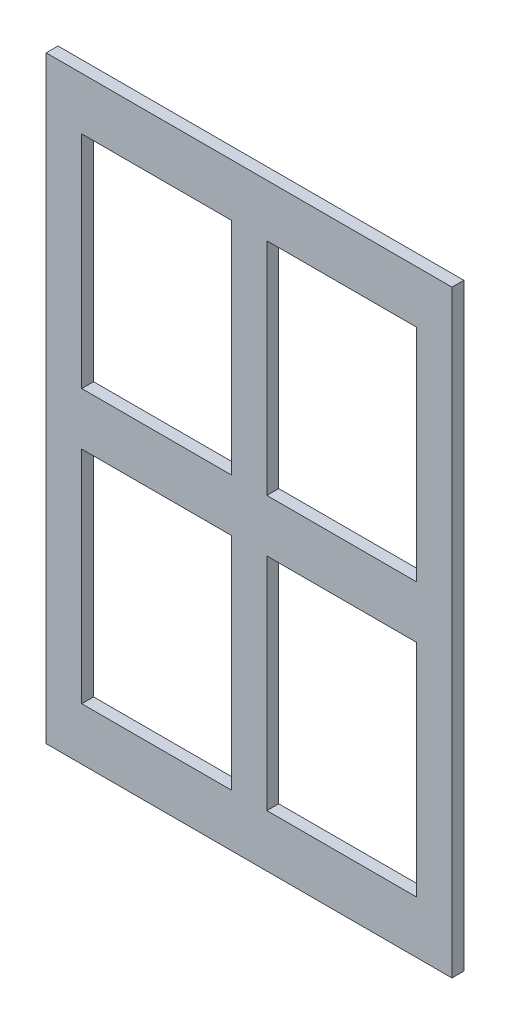
SolidWorks part; units mm, degrees
ref_plane "Front Plane" through (0, 0, 0) normal (0, 0, 1) x (1, 0, 0)
ref_plane "Top Plane" through (0, 0, 0) normal (0, 1, 0) x (1, 0, 0)
ref_plane "Right Plane" through (0, 0, 0) normal (1, 0, 0) x (0, 0, -1)
sketch "Sketch1" plane through (0, 0, 0) normal (0, 0, 1) x (1, 0, 0)
  line L1 (-68.5, -101) -> (68.5, -101)
  line L2 (-68.5, -101) -> (-68.5, 101)
  line L3 (-68.5, 101) -> (68.5, 101)
  line L4 (68.5, -101) -> (68.5, 101)
  line L5 (-68.5, -101) -> (68.5, 101) construction
  line L6 (-68.5, 101) -> (68.5, -101) construction
  line L7 (-56.5, 83.3066) -> (-6, 83.3066)
  line L8 (-56.5, 83.3066) -> (-56.5, 8.8467)
  line L9 (-56.5, 8.8467) -> (-6, 8.8467)
  line L10 (-6, 83.3066) -> (-6, 8.8467)
  line L11 (-56.5, 83.3066) -> (-6, 8.8467) construction
  line L12 (-56.5, 8.8467) -> (-6, 83.3066) construction
  line L13 (56.5, 83.3066) -> (6, 83.3066)
  line L14 (56.5, 83.3066) -> (56.5, 8.8467)
  line L15 (56.5, 8.8467) -> (6, 8.8467)
  line L16 (6, 83.3066) -> (6, 8.8467)
  line L17 (56.5, 83.3066) -> (6, 8.8467) construction
  line L18 (56.5, 8.8467) -> (6, 83.3066) construction
  line L19 (-56.5, -83.3066) -> (-6, -83.3066)
  line L20 (-56.5, -83.3066) -> (-56.5, -8.8467)
  line L21 (-56.5, -8.8467) -> (-6, -8.8467)
  line L22 (-6, -83.3066) -> (-6, -8.8467)
  line L23 (-56.5, -83.3066) -> (-6, -8.8467) construction
  line L24 (-56.5, -8.8467) -> (-6, -83.3066) construction
  line L25 (56.5, -83.3066) -> (6, -83.3066)
  line L26 (56.5, -83.3066) -> (56.5, -8.8467)
  line L27 (56.5, -8.8467) -> (6, -8.8467)
  line L28 (6, -83.3066) -> (6, -8.8467)
  line L29 (56.5, -83.3066) -> (6, -8.8467) construction
  line L30 (56.5, -8.8467) -> (6, -83.3066) construction
  point P0 (0, 0)
  point P6 (-31.25, 46.0766)
  point P11 (31.25, 46.0766)
  point P16 (-31.25, -46.0766)
  point P21 (31.25, -46.0766)
  dimension "D1" = 202
  dimension "D2" = 137
  dimension "D3" = 12
  dimension "D4" = 12
  dimension "D5" = 12
extrude "Boss-Extrude1" add sketch "Sketch1" along normal blind 4
